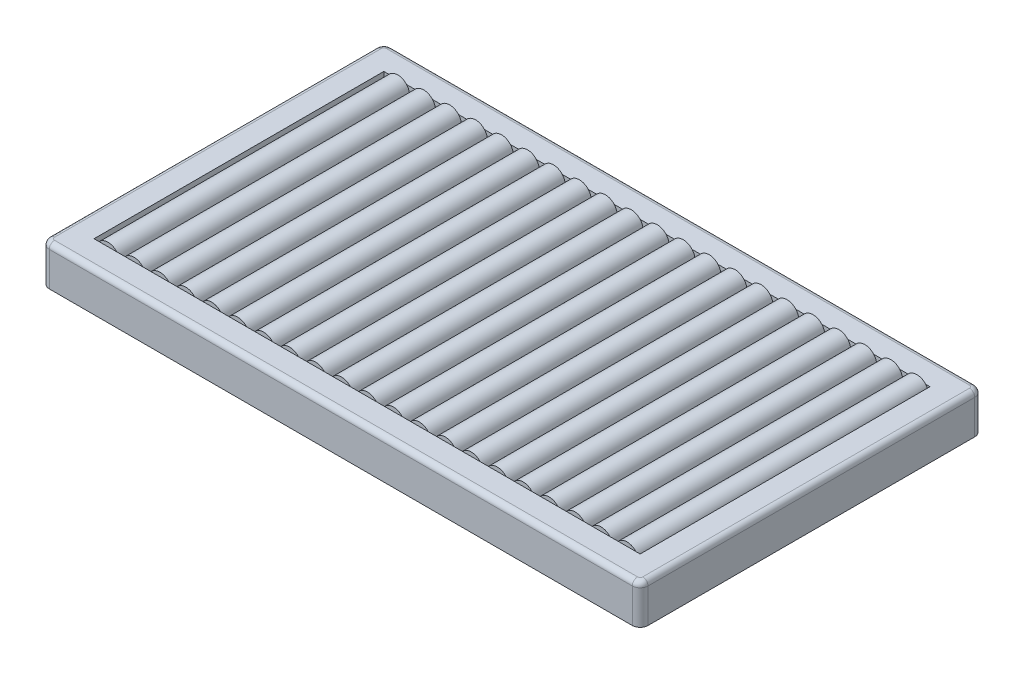
SolidWorks part; units mm, degrees
ref_plane "前视基准面" through (0, 0, 0) normal (0, 0, 1) x (1, 0, 0)
ref_plane "上视基准面" through (0, 0, 0) normal (0, 1, 0) x (1, 0, 0)
ref_plane "右视基准面" through (0, 0, 0) normal (1, 0, 0) x (0, 0, -1)
sketch "草图1" plane through (0, 0, 0) normal (0, 1, 0) x (1, 0, 0)
  line L0 (-65.4628, 64.2038) -> (-65.4628, -59.7962)
  line L1 (158.8236, -62.7962) -> (-62.4628, -62.7962)
  line L4 (161.8236, 64.2038) -> (161.8236, -59.7962)
  line L5 (158.8236, 67.2038) -> (-62.4628, 67.2038)
  circle A0 centre (-11.8196, -57.7962) radius 1.5
  circle A1 centre (108.1804, -57.7962) radius 1.5
  circle A2 centre (108.1804, 62.2038) radius 1.5
  circle A3 centre (-11.8196, 62.2038) radius 1.5
  arc A4 (-62.4628, 67.2038) -> (-65.4628, 64.2038) centre (-62.4628, 64.2038) ccw
  arc A5 (161.8236, 64.2038) -> (158.8236, 67.2038) centre (158.8236, 64.2038) ccw
  arc A6 (161.8236, -59.7962) -> (158.8236, -62.7962) centre (158.8236, -59.7962) cw
  arc A7 (-62.4628, -62.7962) -> (-65.4628, -59.7962) centre (-62.4628, -59.7962) cw
  point P16 (161.8236, 2.2038)
  dimension "D1" = 3
  dimension "D2" = 3
extrude "凸台-拉伸1" add sketch "草图1" along normal blind 5
sketch "草图2" plane through (0, 5, 0) normal (0, 1, 0) x (1, 0, 0)
  line L0 (48.1804, -62.7962) -> (158.8236, -62.7962)
  line L1 (-62.4628, -62.7962) -> (158.8236, -62.7962) construction
  line L2 (161.8236, -59.7962) -> (161.8236, 64.2038)
  line L3 (48.1804, -62.7962) -> (-62.4628, -62.7962)
  line L4 (-65.4628, -59.7962) -> (-65.4628, 64.2038)
  line L5 (-62.4628, 67.2038) -> (158.8236, 67.2038)
  line L6 (48.1804, -52.7962) -> (151.8236, -52.7962)
  line L7 (151.8236, -52.7962) -> (151.8236, 57.2038)
  line L8 (-55.4628, 57.2038) -> (151.8236, 57.2038)
  line L9 (-55.4628, -52.7962) -> (-55.4628, 57.2038)
  line L10 (48.1804, -52.7962) -> (-55.4628, -52.7962)
  arc A0 (158.8236, -62.7962) -> (161.8236, -59.7962) centre (158.8236, -59.7962) ccw
  arc A1 (158.8236, 67.2038) -> (161.8236, 64.2038) centre (158.8236, 64.2038) cw
  arc A2 (-65.4628, 64.2038) -> (-62.4628, 67.2038) centre (-62.4628, 64.2038) cw
  arc A3 (-65.4628, -59.7962) -> (-62.4628, -62.7962) centre (-62.4628, -59.7962) ccw
  arc A4 (151.8236, -52.7962) -> (151.8236, -52.7962) centre (151.8236, -52.7962) ccw
  arc A5 (151.8236, 57.2038) -> (151.8236, 57.2038) centre (151.8236, 57.2038) cw
  arc A6 (-55.4628, 57.2038) -> (-55.4628, 57.2038) centre (-55.4628, 57.2038) cw
  arc A7 (-55.4628, -52.7962) -> (-55.4628, -52.7962) centre (-55.4628, -52.7962) ccw
  dimension "D1" = 3
  dimension "D2" = 3
  dimension "D3" = 3
  dimension "D4" = 3
  dimension "D5" = 10
extrude "凸台-拉伸2" add sketch "草图2" along normal blind 10
fillet "圆角1" radius 2 8 edges at (160.9449, 15, 61.9175) (48.1804, 15, 62.7962) (-64.5841, 15, 61.9175) (-65.4628, 15, -2.2038) (-64.5841, 15, -66.3251) (48.1804, 15, -67.2038) (160.9449, 15, -66.3251) (161.8236, 15, -2.2038)
sketch "草图4" plane through (0, 0, 52.7962) normal (0, 0, -1) x (-1, 0, 0)
  circle A0 centre (-146.8236, 12) radius 4.5
  circle A1 centre (-136.9736, 12) radius 4.5
  circle A2 centre (-127.1236, 12) radius 4.5
  circle A3 centre (-117.2736, 12) radius 4.5
  circle A4 centre (-107.4236, 12) radius 4.5
  circle A5 centre (-97.5736, 12) radius 4.5
  circle A6 centre (-87.7236, 12) radius 4.5
  circle A7 centre (-77.8736, 12) radius 4.5
  circle A8 centre (-68.0236, 12) radius 4.5
  circle A9 centre (-58.1736, 12) radius 4.5
  circle A10 centre (-48.3236, 12) radius 4.5
  circle A11 centre (-38.4736, 12) radius 4.5
  circle A12 centre (-28.6236, 12) radius 4.5
  circle A13 centre (-18.7736, 12) radius 4.5
  circle A14 centre (-8.9236, 12) radius 4.5
  circle A15 centre (0.9264, 12) radius 4.5
  circle A16 centre (10.7764, 12) radius 4.5
  circle A17 centre (20.6264, 12) radius 4.5
  circle A18 centre (30.4764, 12) radius 4.5
  circle A19 centre (40.3264, 12) radius 4.5
  circle A20 centre (50.1764, 12) radius 4.5
  dimension "D1" = 21
extrude "凸台-拉伸4" add sketch "草图4" along normal up to surface (110 mm away) up to face at (48.1804, 10, -57.2038)
